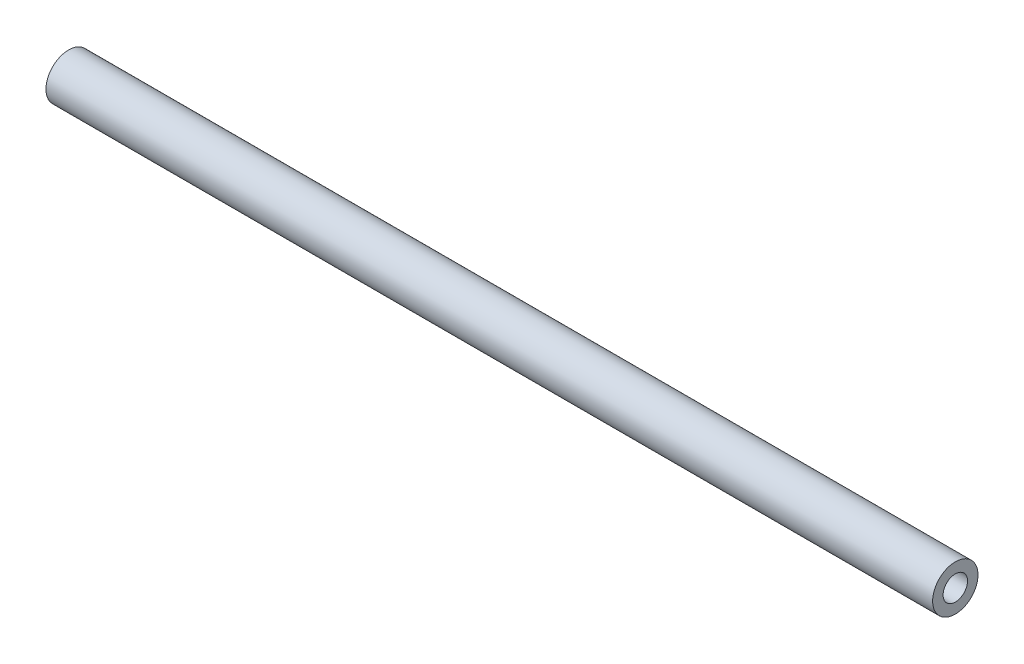
SolidWorks part; units mm, degrees
ref_plane "Front Plane" through (0, 0, 0) normal (0, 0, 1) x (1, 0, 0)
ref_plane "Top Plane" through (0, 0, 0) normal (0, 1, 0) x (1, 0, 0)
ref_plane "Right Plane" through (0, 0, 0) normal (1, 0, 0) x (0, 0, -1)
sketch "Sketch1" plane through (0, 0, 0) normal (1, 0, 0) x (0, 0, -1)
  circle A0 centre (0, 0) radius 6.5
  circle A1 centre (0, 0) radius 3.5
  dimension "D1" = 7
  dimension "D2" = 13
extrude "Boss-Extrude1" add sketch "Sketch1" along normal mid plane 254
